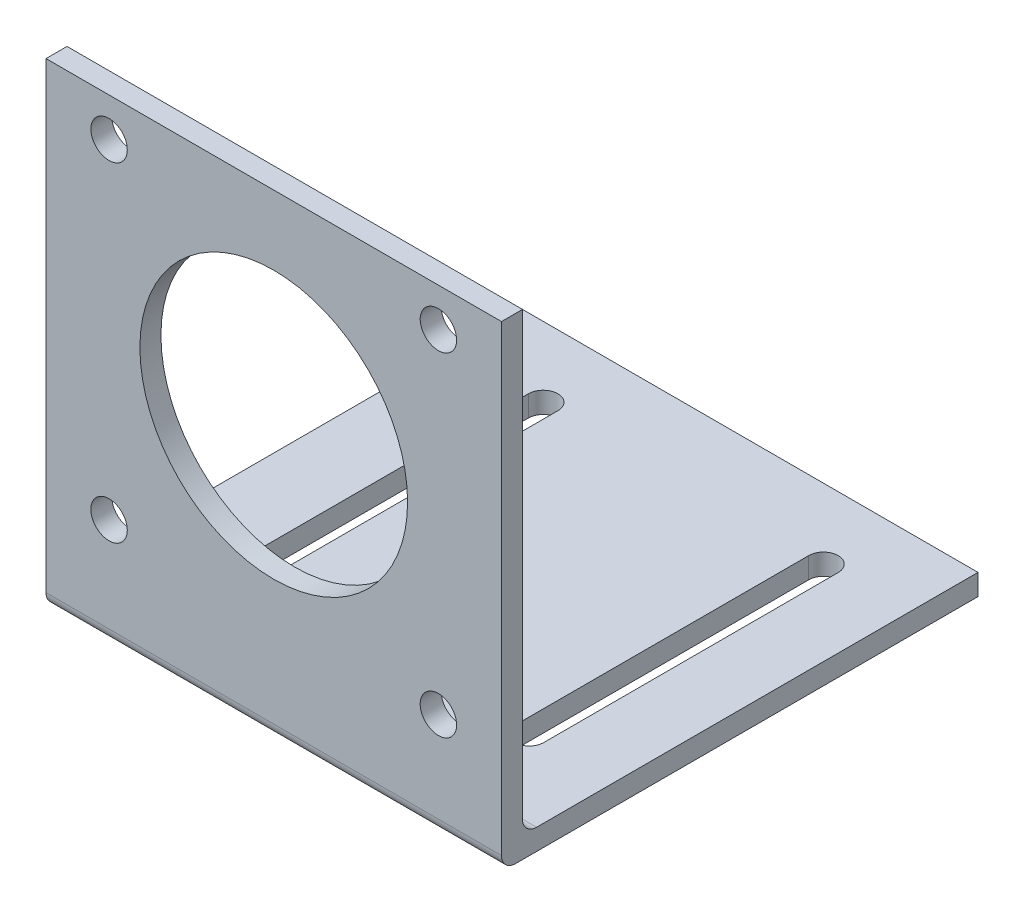
SolidWorks part; units mm, degrees
ref_plane "Спереди" through (0, 0, 0) normal (0, 0, 1) x (1, 0, 0)
ref_plane "Сверху" through (0, 0, 0) normal (0, 1, 0) x (1, 0, 0)
ref_plane "Справа" through (0, 0, 0) normal (1, 0, 0) x (0, 0, -1)
sketch "Эскиз1" plane through (0, 0, 0) normal (1, 0, 0) x (0, 0, -1)
  line L0 (0, 68) -> (0, 2)
  line L1 (2, 0) -> (68, 0)
  line L2 (68, 0) -> (68, 3)
  line L3 (68, 3) -> (5, 3)
  line L4 (3, 5) -> (3, 68)
  line L7 (0, 68) -> (3, 68)
  arc A0 (5, 3) -> (3, 5) centre (5, 5) cw
  arc A1 (0, 2) -> (2, 0) centre (2, 2) ccw
  point P11 (0, 0)
  dimension "D5" = 2
  dimension "D1" = 3
  dimension "D2" = 3
  dimension "D3" = 68
  dimension "D4" = 68
extrude "Бобышка-Вытянуть1" add sketch "Эскиз1" along normal blind 65
sketch "Эскиз2" plane through (0, 3, 0) normal (0, 1, 0) x (1, 0, 0)
  line L0 (32.9455, 76.1759) -> (32.9455, 17.1478) construction
  line L1 (52.9455, 76.1759) -> (52.9455, 17.1478) construction
  line L2 (52.9455, 58) -> (52.9455, 16) construction
  line L3 (55.0455, 58) -> (55.0455, 16)
  line L4 (50.8455, 58) -> (50.8455, 16)
  line L5 (65, 68) -> (0, 68) construction
  line L6 (12.9455, 58) -> (12.9455, 16) construction
  line L7 (10.8455, 58) -> (10.8455, 16)
  line L8 (15.0455, 58) -> (15.0455, 16)
  arc A0 (55.0455, 58) -> (50.8455, 58) centre (52.9455, 58) ccw
  arc A1 (50.8455, 16) -> (55.0455, 16) centre (52.9455, 16) ccw
  arc A2 (10.8455, 58) -> (15.0455, 58) centre (12.9455, 58) cw
  arc A3 (15.0455, 16) -> (10.8455, 16) centre (12.9455, 16) cw
  point P6 (52.9455, 37)
  point P15 (12.9455, 37)
  point P20 (0, 0)
  point P21 (0, 0)
  dimension "D2" = 10
  dimension "D1" = 20
extrude "Вырез-Вытянуть1" cut sketch "Эскиз2" against normal through all
sketch "Эскиз3" plane through (0, 0, 0) normal (0, 0, 1) x (1, 0, 0)
  line L0 (65, 68) -> (0, 68) construction
  line L1 (0, 68) -> (0, 2) construction
  circle A0 centre (32.5, 39) radius 19.1
  circle A1 centre (9, 62.5) radius 2.6
  circle A2 centre (56, 62.5) radius 2.6
  circle A3 centre (55.9966, 14.9347) radius 2.6
  circle A4 centre (9, 15.5) radius 2.6
  dimension "D1" = 38.2
  dimension "D4" = 5.2
  dimension "D5" = 5.2
  dimension "D6" = 5.2
  dimension "D7" = 5.2
  dimension "D8" = 47
  dimension "D9" = 47
  dimension "D10" = 47
  dimension "D11" = 23.5
  dimension "D12" = 23.5
  dimension "D2" = 29
  dimension "D3" = 32.5
extrude "Вырез-Вытянуть2" cut sketch "Эскиз3" against normal through all
